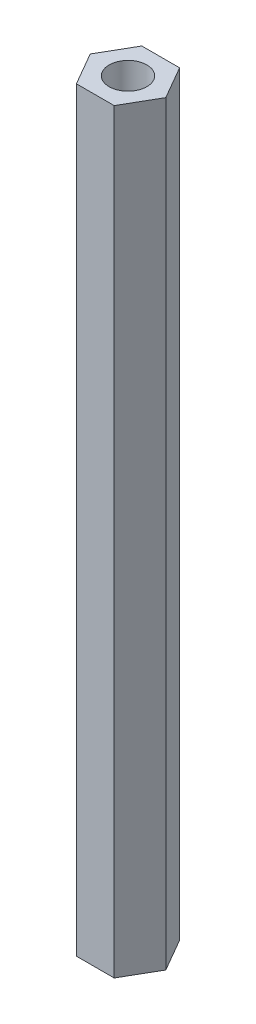
SolidWorks part; units mm, degrees
material "Stainless Steel (ferritic)"
ref_plane "Front Plane" through (0, 0, 0) normal (0, 0, 1) x (1, 0, 0)
ref_plane "Top Plane" through (0, 0, 0) normal (0, 1, 0) x (1, 0, 0)
ref_plane "Right Plane" through (0, 0, 0) normal (1, 0, 0) x (0, 0, -1)
other "Center of Mass"
sketch "Sketch2" plane through (0, 0, 0) normal (0, 1, 0) x (1, 0, 0)
  line L1 (3, 0) -> (1.5, 2.5981)
  line L2 (1.5, 2.5981) -> (-1.5, 2.5981)
  line L3 (-1.5, 2.5981) -> (-3, 0)
  line L4 (-3, 0) -> (-1.5, -2.5981)
  line L5 (-1.5, -2.5981) -> (1.5, -2.5981)
  line L6 (1.5, -2.5981) -> (3, 0)
  circle A0 centre (0, 0) radius 2.5981 construction
  circle A1 centre (0, 0) radius 1.5
  dimension "D2" = 3
  dimension "D1" = 6
extrude "Boss-Extrude1" add sketch "Sketch2" along normal blind 60
